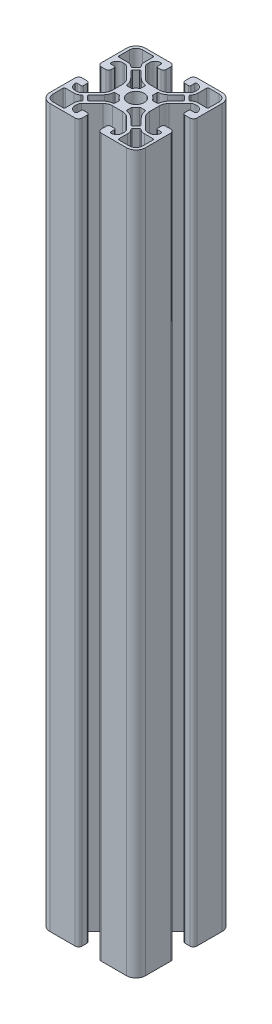
SolidWorks part; units mm, degrees
ref_plane "Front Plane" through (0, 0, 0) normal (0, 0, 1) x (1, 0, 0)
ref_plane "Top Plane" through (0, 0, 0) normal (0, 1, 0) x (1, 0, 0)
ref_plane "Right Plane" through (0, 0, 0) normal (1, 0, 0) x (0, 0, -1)
sketch "Sketch1" plane through (0, 0, 0) normal (0, -1, 0) x (1, 0, 0)
  line L0 (8.9216, 4.9716) -> (13.3642, 9.4142)
  line L1 (14.7784, 10) -> (15.5, 10)
  line L2 (17.5, 7) -> (16, 7)
  line L3 (15.5, 6.5) -> (15.5, 5)
  line L4 (16.5, 4) -> (18.5, 4)
  line L5 (20, 5.5) -> (20, 16)
  line L7 (16, 20) -> (5.5, 20)
  line L8 (4, 18.5) -> (4, 16.5)
  line L9 (5, 15.5) -> (6.5, 15.5)
  line L10 (7, 16) -> (7, 17.5)
  line L11 (10, 15.5) -> (10, 14.7784)
  line L12 (9.4142, 13.3642) -> (4.9716, 8.9216)
  line L13 (2.5, 6.181) -> (2.5, 4.6125)
  line L21 (10.8696, 9.4984) -> (9.4984, 10.8696)
  line L22 (4.6126, 2.5) -> (6.181, 2.5)
  line L23 (10.5378, 12.7378) -> (10.3098, 12.4411)
  line L24 (11.2, 18.3) -> (11.2, 14.6871)
  line L25 (16, 18.8) -> (11.7, 18.8)
  line L26 (18.8, 11.7) -> (18.8, 16)
  line L27 (14.6871, 11.2) -> (18.3, 11.2)
  line L37 (12.4411, 10.3098) -> (12.7378, 10.5378)
  line L38 (10.3528, 11.783) -> (11.783, 10.3528)
  line L39 (4.9716, -8.9216) -> (9.4142, -13.3642)
  line L43 (10, -14.7784) -> (10, -15.5)
  line L44 (7, -17.5) -> (7, -16)
  line L45 (6.5, -15.5) -> (5, -15.5)
  line L47 (4, -16.5) -> (4, -18.5)
  line L48 (5.5, -20) -> (16, -20)
  line L49 (20, -16) -> (20, -5.5)
  line L50 (18.5, -4) -> (16.5, -4)
  line L51 (15.5, -5) -> (15.5, -6.5)
  line L52 (16, -7) -> (17.5, -7)
  line L53 (15.5, -10) -> (14.7784, -10)
  line L54 (13.3642, -9.4142) -> (8.9216, -4.9716)
  line L55 (6.181, -2.5) -> (4.6125, -2.5)
  line L56 (9.4984, -10.8696) -> (10.8696, -9.4984)
  line L57 (2.5, -4.6126) -> (2.5, -6.181)
  line L58 (12.7378, -10.5378) -> (12.4411, -10.3098)
  line L59 (18.3, -11.2) -> (14.6871, -11.2)
  line L60 (18.8, -16) -> (18.8, -11.7)
  line L61 (11.7, -18.8) -> (16, -18.8)
  line L62 (11.2, -14.6871) -> (11.2, -18.3)
  line L63 (10.3098, -12.4411) -> (10.5378, -12.7378)
  line L64 (11.783, -10.3528) -> (10.3528, -11.783)
  line L65 (-8.9216, -4.9716) -> (-13.3642, -9.4142)
  line L66 (-14.7784, -10) -> (-15.5, -10)
  line L67 (-17.5, -7) -> (-16, -7)
  line L68 (-15.5, -6.5) -> (-15.5, -5)
  line L69 (-16.5, -4) -> (-18.5, -4)
  line L70 (-20, -5.5) -> (-20, -16)
  line L71 (-16, -20) -> (-5.5, -20)
  line L72 (-4, -18.5) -> (-4, -16.5)
  line L73 (-5, -15.5) -> (-6.5, -15.5)
  line L74 (-7, -16) -> (-7, -17.5)
  line L75 (-10, -15.5) -> (-10, -14.7784)
  line L76 (-9.4142, -13.3642) -> (-4.9716, -8.9216)
  line L77 (-2.5, -6.181) -> (-2.5, -4.6125)
  line L78 (-10.8696, -9.4984) -> (-9.4984, -10.8696)
  line L79 (-4.6126, -2.5) -> (-6.181, -2.5)
  line L80 (-10.5378, -12.7378) -> (-10.3098, -12.4411)
  line L81 (-11.2, -18.3) -> (-11.2, -14.6871)
  line L82 (-16, -18.8) -> (-11.7, -18.8)
  line L83 (-18.8, -11.7) -> (-18.8, -16)
  line L84 (-14.6871, -11.2) -> (-18.3, -11.2)
  line L85 (-12.4411, -10.3098) -> (-12.7378, -10.5378)
  line L86 (-10.3528, -11.783) -> (-11.783, -10.3528)
  line L87 (-2.1431, 7.75) -> (2.1431, 7.75)
  line L88 (7.75, 2.1431) -> (7.75, -2.1431)
  line L89 (2.1431, -7.75) -> (-2.1431, -7.75)
  line L90 (-7.75, -2.1431) -> (-7.75, 2.1431)
  line L125 (-4.9716, 8.9216) -> (-9.4142, 13.3642)
  line L126 (-10, 14.7784) -> (-10, 15.5)
  line L127 (-7, 17.5) -> (-7, 16)
  line L128 (-6.5, 15.5) -> (-5, 15.5)
  line L129 (-4, 16.5) -> (-4, 18.5)
  line L130 (-5.5, 20) -> (-16, 20)
  line L131 (-20, 16) -> (-20, 5.5)
  line L132 (-18.5, 4) -> (-16.5, 4)
  line L133 (-15.5, 5) -> (-15.5, 6.5)
  line L134 (-16, 7) -> (-17.5, 7)
  line L135 (-15.5, 10) -> (-14.7784, 10)
  line L136 (-13.3642, 9.4142) -> (-8.9216, 4.9716)
  line L170 (-6.181, 2.5) -> (-4.6125, 2.5)
  line L171 (-9.4984, 10.8696) -> (-10.8696, 9.4984)
  line L172 (-2.5, 4.6126) -> (-2.5, 6.181)
  line L184 (-12.7378, 10.5378) -> (-12.4411, 10.3098)
  line L185 (-18.3, 11.2) -> (-14.6871, 11.2)
  line L186 (-18.8, 16) -> (-18.8, 11.7)
  line L187 (-11.7, 18.8) -> (-16, 18.8)
  line L188 (-11.2, 14.6871) -> (-11.2, 18.3)
  line L189 (-10.3098, 12.4411) -> (-10.5378, 12.7378)
  line L190 (-11.783, 10.3528) -> (-10.3528, 11.783)
  arc A0 (0, 3.4) -> (0, -3.4) centre (0, 0) ccw
  arc A1 (0, -3.4) -> (0, 3.4) centre (0, 0) ccw
  arc A2 (8.9216, 4.9716) -> (7.75, 2.1431) centre (11.75, 2.1431) ccw
  arc A3 (14.7784, 10) -> (13.3642, 9.4142) centre (14.7784, 8) ccw
  arc A4 (-3.4, 0) -> (3.4, 0) centre (0, 0) ccw
  arc A5 (3.4, 0) -> (-3.4, 0) centre (0, 0) ccw
  arc A6 (18, 7.5) -> (15.5, 10) centre (15.5, 7.5) ccw
  arc A7 (17.5, 7) -> (18, 7.5) centre (17.5, 7.5) ccw
  arc A8 (16, 7) -> (15.5, 6.5) centre (16, 6.5) ccw
  arc A9 (15.5, 5) -> (16.5, 4) centre (16.5, 5) ccw
  arc A10 (18.5, 4) -> (20, 5.5) centre (18.5, 5.5) ccw
  arc A11 (20, 16) -> (16, 20) centre (16, 16) ccw
  arc A12 (5.5, 20) -> (4, 18.5) centre (5.5, 18.5) ccw
  arc A13 (4, 16.5) -> (5, 15.5) centre (5, 16.5) ccw
  arc A21 (6.5, 15.5) -> (7, 16) centre (6.5, 16) ccw
  arc A22 (7.5, 18) -> (7, 17.5) centre (7.5, 17.5) ccw
  arc A23 (10, 15.5) -> (7.5, 18) centre (7.5, 15.5) ccw
  arc A24 (9.4142, 13.3642) -> (10, 14.7784) centre (8, 14.7784) ccw
  arc A25 (2.1431, 7.75) -> (4.9716, 8.9216) centre (2.1431, 11.75) ccw
  arc A26 (2.5, 4.6125) -> (2.7274, 4.1934) centre (3, 4.6125) ccw
  arc A27 (2.9293, 6.676) -> (2.5, 6.181) centre (3, 6.181) ccw
  arc A35 (2.9293, 6.676) -> (5.3722, 7.7078) centre (2.1944, 11.8238) ccw
  arc A36 (5.3722, 7.7078) -> (8.7744, 10.8518) centre (-10.6389, 28.4463) ccw
  arc A37 (9.4984, 10.8696) -> (8.7744, 10.8518) centre (9.1449, 10.516) ccw
  arc A38 (10.8518, 8.7744) -> (10.8696, 9.4984) centre (10.516, 9.1449) ccw
  arc A39 (10.8518, 8.7744) -> (7.7078, 5.3722) centre (28.4463, -10.6389) ccw
  arc A40 (7.7078, 5.3722) -> (6.676, 2.9293) centre (11.8238, 2.1944) ccw
  arc A41 (6.181, 2.5) -> (6.676, 2.9293) centre (6.181, 3) ccw
  arc A42 (4.1934, 2.7274) -> (4.6126, 2.5) centre (4.6126, 3) ccw
  arc A43 (4.1934, 2.7274) -> (2.7274, 4.1934) centre (0.0017, 0.0017) ccw
  arc A44 (10.3098, 12.4411) -> (10.3528, 11.783) centre (10.7064, 12.1365) ccw
  arc A45 (10.5378, 12.7378) -> (11.2, 14.6871) centre (8, 14.6871) ccw
  arc A46 (11.7, 18.8) -> (11.2, 18.3) centre (11.7, 18.3) ccw
  arc A47 (18.8, 16) -> (16, 18.8) centre (16, 16) ccw
  arc A48 (18.3, 11.2) -> (18.8, 11.7) centre (18.3, 11.7) ccw
  arc A49 (14.6871, 11.2) -> (12.7378, 10.5378) centre (14.6871, 8) ccw
  arc A60 (11.783, 10.3528) -> (12.4411, 10.3098) centre (12.1365, 10.7064) ccw
  arc A61 (3.4, 0) -> (-3.4, 0) centre (0, 0) ccw
  arc A62 (-3.4, 0) -> (3.4, 0) centre (0, 0) ccw
  arc A63 (4.9716, -8.9216) -> (2.1431, -7.75) centre (2.1431, -11.75) ccw
  arc A64 (10, -14.7784) -> (9.4142, -13.3642) centre (8, -14.7784) ccw
  arc A65 (7.5, -18) -> (10, -15.5) centre (7.5, -15.5) ccw
  arc A66 (7, -17.5) -> (7.5, -18) centre (7.5, -17.5) ccw
  arc A67 (7, -16) -> (6.5, -15.5) centre (6.5, -16) ccw
  arc A68 (5, -15.5) -> (4, -16.5) centre (5, -16.5) ccw
  arc A69 (4, -18.5) -> (5.5, -20) centre (5.5, -18.5) ccw
  arc A70 (16, -20) -> (20, -16) centre (16, -16) ccw
  arc A71 (20, -5.5) -> (18.5, -4) centre (18.5, -5.5) ccw
  arc A72 (16.5, -4) -> (15.5, -5) centre (16.5, -5) ccw
  arc A73 (15.5, -6.5) -> (16, -7) centre (16, -6.5) ccw
  arc A74 (18, -7.5) -> (17.5, -7) centre (17.5, -7.5) ccw
  arc A75 (15.5, -10) -> (18, -7.5) centre (15.5, -7.5) ccw
  arc A76 (13.3642, -9.4142) -> (14.7784, -10) centre (14.7784, -8) ccw
  arc A77 (7.75, -2.1431) -> (8.9216, -4.9716) centre (11.75, -2.1431) ccw
  arc A78 (4.6125, -2.5) -> (4.1934, -2.7274) centre (4.6125, -3) ccw
  arc A79 (6.676, -2.9293) -> (6.181, -2.5) centre (6.181, -3) ccw
  arc A80 (6.676, -2.9293) -> (7.7078, -5.3722) centre (11.8238, -2.1944) ccw
  arc A81 (7.7078, -5.3722) -> (10.8518, -8.7744) centre (28.4463, 10.6389) ccw
  arc A82 (10.8696, -9.4984) -> (10.8518, -8.7744) centre (10.516, -9.1449) ccw
  arc A83 (8.7744, -10.8518) -> (9.4984, -10.8696) centre (9.1449, -10.516) ccw
  arc A84 (8.7744, -10.8518) -> (5.3722, -7.7078) centre (-10.6389, -28.4463) ccw
  arc A85 (5.3722, -7.7078) -> (2.9293, -6.676) centre (2.1944, -11.8238) ccw
  arc A86 (2.5, -6.181) -> (2.9293, -6.676) centre (3, -6.181) ccw
  arc A87 (2.7274, -4.1934) -> (2.5, -4.6126) centre (3, -4.6126) ccw
  arc A88 (2.7274, -4.1934) -> (4.1934, -2.7274) centre (0.0017, -0.0017) ccw
  arc A89 (12.4411, -10.3098) -> (11.783, -10.3528) centre (12.1365, -10.7064) ccw
  arc A90 (12.7378, -10.5378) -> (14.6871, -11.2) centre (14.6871, -8) ccw
  arc A91 (18.8, -11.7) -> (18.3, -11.2) centre (18.3, -11.7) ccw
  arc A92 (16, -18.8) -> (18.8, -16) centre (16, -16) ccw
  arc A93 (11.2, -18.3) -> (11.7, -18.8) centre (11.7, -18.3) ccw
  arc A94 (11.2, -14.6871) -> (10.5378, -12.7378) centre (8, -14.6871) ccw
  arc A95 (10.3528, -11.783) -> (10.3098, -12.4411) centre (10.7064, -12.1365) ccw
  arc A96 (0, -3.4) -> (0, 3.4) centre (0, 0) ccw
  arc A97 (0, 3.4) -> (0, -3.4) centre (0, 0) ccw
  arc A98 (-8.9216, -4.9716) -> (-7.75, -2.1431) centre (-11.75, -2.1431) ccw
  arc A99 (-14.7784, -10) -> (-13.3642, -9.4142) centre (-14.7784, -8) ccw
  arc A100 (-18, -7.5) -> (-15.5, -10) centre (-15.5, -7.5) ccw
  arc A101 (-17.5, -7) -> (-18, -7.5) centre (-17.5, -7.5) ccw
  arc A102 (-16, -7) -> (-15.5, -6.5) centre (-16, -6.5) ccw
  arc A103 (-15.5, -5) -> (-16.5, -4) centre (-16.5, -5) ccw
  arc A104 (-18.5, -4) -> (-20, -5.5) centre (-18.5, -5.5) ccw
  arc A105 (-20, -16) -> (-16, -20) centre (-16, -16) ccw
  arc A106 (-5.5, -20) -> (-4, -18.5) centre (-5.5, -18.5) ccw
  arc A107 (-4, -16.5) -> (-5, -15.5) centre (-5, -16.5) ccw
  arc A108 (-6.5, -15.5) -> (-7, -16) centre (-6.5, -16) ccw
  arc A109 (-7.5, -18) -> (-7, -17.5) centre (-7.5, -17.5) ccw
  arc A110 (-10, -15.5) -> (-7.5, -18) centre (-7.5, -15.5) ccw
  arc A111 (-9.4142, -13.3642) -> (-10, -14.7784) centre (-8, -14.7784) ccw
  arc A112 (-2.1431, -7.75) -> (-4.9716, -8.9216) centre (-2.1431, -11.75) ccw
  arc A113 (-2.5, -4.6125) -> (-2.7274, -4.1934) centre (-3, -4.6125) ccw
  arc A114 (-2.9293, -6.676) -> (-2.5, -6.181) centre (-3, -6.181) ccw
  arc A115 (-2.9293, -6.676) -> (-5.3722, -7.7078) centre (-2.1944, -11.8238) ccw
  arc A116 (-5.3722, -7.7078) -> (-8.7744, -10.8518) centre (10.6389, -28.4463) ccw
  arc A117 (-9.4984, -10.8696) -> (-8.7744, -10.8518) centre (-9.1449, -10.516) ccw
  arc A118 (-10.8518, -8.7744) -> (-10.8696, -9.4984) centre (-10.516, -9.1449) ccw
  arc A119 (-10.8518, -8.7744) -> (-7.7078, -5.3722) centre (-28.4463, 10.6389) ccw
  arc A144 (-4.9716, 8.9216) -> (-2.1431, 7.75) centre (-2.1431, 11.75) ccw
  arc A145 (-10, 14.7784) -> (-9.4142, 13.3642) centre (-8, 14.7784) ccw
  arc A146 (-7.5, 18) -> (-10, 15.5) centre (-7.5, 15.5) ccw
  arc A147 (-7, 17.5) -> (-7.5, 18) centre (-7.5, 17.5) ccw
  arc A148 (-7, 16) -> (-6.5, 15.5) centre (-6.5, 16) ccw
  arc A149 (-5, 15.5) -> (-4, 16.5) centre (-5, 16.5) ccw
  arc A150 (-4, 18.5) -> (-5.5, 20) centre (-5.5, 18.5) ccw
  arc A151 (-16, 20) -> (-20, 16) centre (-16, 16) ccw
  arc A152 (-20, 5.5) -> (-18.5, 4) centre (-18.5, 5.5) ccw
  arc A153 (-16.5, 4) -> (-15.5, 5) centre (-16.5, 5) ccw
  arc A154 (-15.5, 6.5) -> (-16, 7) centre (-16, 6.5) ccw
  arc A155 (-18, 7.5) -> (-17.5, 7) centre (-17.5, 7.5) ccw
  arc A156 (-15.5, 10) -> (-18, 7.5) centre (-15.5, 7.5) ccw
  arc A157 (-13.3642, 9.4142) -> (-14.7784, 10) centre (-14.7784, 8) ccw
  arc A158 (-7.75, 2.1431) -> (-8.9216, 4.9716) centre (-11.75, 2.1431) ccw
  arc A181 (-7.7078, -5.3722) -> (-6.676, -2.9293) centre (-11.8238, -2.1944) ccw
  arc A182 (-6.181, -2.5) -> (-6.676, -2.9293) centre (-6.181, -3) ccw
  arc A183 (-4.1934, -2.7274) -> (-4.6126, -2.5) centre (-4.6126, -3) ccw
  arc A184 (-4.1934, -2.7274) -> (-2.7274, -4.1934) centre (-0.0017, -0.0017) ccw
  arc A185 (-10.3098, -12.4411) -> (-10.3528, -11.783) centre (-10.7064, -12.1365) ccw
  arc A186 (-10.5378, -12.7378) -> (-11.2, -14.6871) centre (-8, -14.6871) ccw
  arc A187 (-11.7, -18.8) -> (-11.2, -18.3) centre (-11.7, -18.3) ccw
  arc A188 (-18.8, -16) -> (-16, -18.8) centre (-16, -16) ccw
  arc A189 (-18.3, -11.2) -> (-18.8, -11.7) centre (-18.3, -11.7) ccw
  arc A190 (-14.6871, -11.2) -> (-12.7378, -10.5378) centre (-14.6871, -8) ccw
  arc A191 (-11.783, -10.3528) -> (-12.4411, -10.3098) centre (-12.1365, -10.7064) ccw
  arc A254 (-4.6125, 2.5) -> (-4.1934, 2.7274) centre (-4.6125, 3) ccw
  arc A255 (-6.676, 2.9293) -> (-6.181, 2.5) centre (-6.181, 3) ccw
  arc A256 (-6.676, 2.9293) -> (-7.7078, 5.3722) centre (-11.8238, 2.1944) ccw
  arc A257 (-7.7078, 5.3722) -> (-10.8518, 8.7744) centre (-28.4463, -10.6389) ccw
  arc A258 (-10.8696, 9.4984) -> (-10.8518, 8.7744) centre (-10.516, 9.1449) ccw
  arc A259 (-8.7744, 10.8518) -> (-9.4984, 10.8696) centre (-9.1449, 10.516) ccw
  arc A260 (-8.7744, 10.8518) -> (-5.3722, 7.7078) centre (10.6389, 28.4463) ccw
  arc A261 (-5.3722, 7.7078) -> (-2.9293, 6.676) centre (-2.1944, 11.8238) ccw
  arc A262 (-2.5, 6.181) -> (-2.9293, 6.676) centre (-3, 6.181) ccw
  arc A263 (-2.7274, 4.1934) -> (-2.5, 4.6126) centre (-3, 4.6126) ccw
  arc A264 (-2.7274, 4.1934) -> (-4.1934, 2.7274) centre (-0.0017, 0.0017) ccw
  arc A268 (-12.4411, 10.3098) -> (-11.783, 10.3528) centre (-12.1365, 10.7064) ccw
  arc A269 (-12.7378, 10.5378) -> (-14.6871, 11.2) centre (-14.6871, 8) ccw
  arc A270 (-18.8, 11.7) -> (-18.3, 11.2) centre (-18.3, 11.7) ccw
  arc A271 (-16, 18.8) -> (-18.8, 16) centre (-16, 16) ccw
  arc A272 (-11.2, 18.3) -> (-11.7, 18.8) centre (-11.7, 18.3) ccw
  arc A273 (-11.2, 14.6871) -> (-10.5378, 12.7378) centre (-8, 14.6871) ccw
  arc A274 (-10.3528, 11.783) -> (-10.3098, 12.4411) centre (-10.7064, 12.1365) ccw
  point P367 (0, 0)
  dimension "D1" = 40
extrude "Boss-Extrude1" add sketch "Sketch1" against normal blind 300 separate body contours L90 A158 L136 A157 L135 A156 A155 L134 A154 L133 A153 L132 A152 L131 A151 L130 A150 L129 A149 L128 A148 L127 A147 A146 L126 A145 L125 A144 L87 A25 L12 A24 L11 A23 A22 L10 A21 L9 A13 L8 A12 L7 A11 L5 A10 L4 A9 L3 A8 L2 A7
